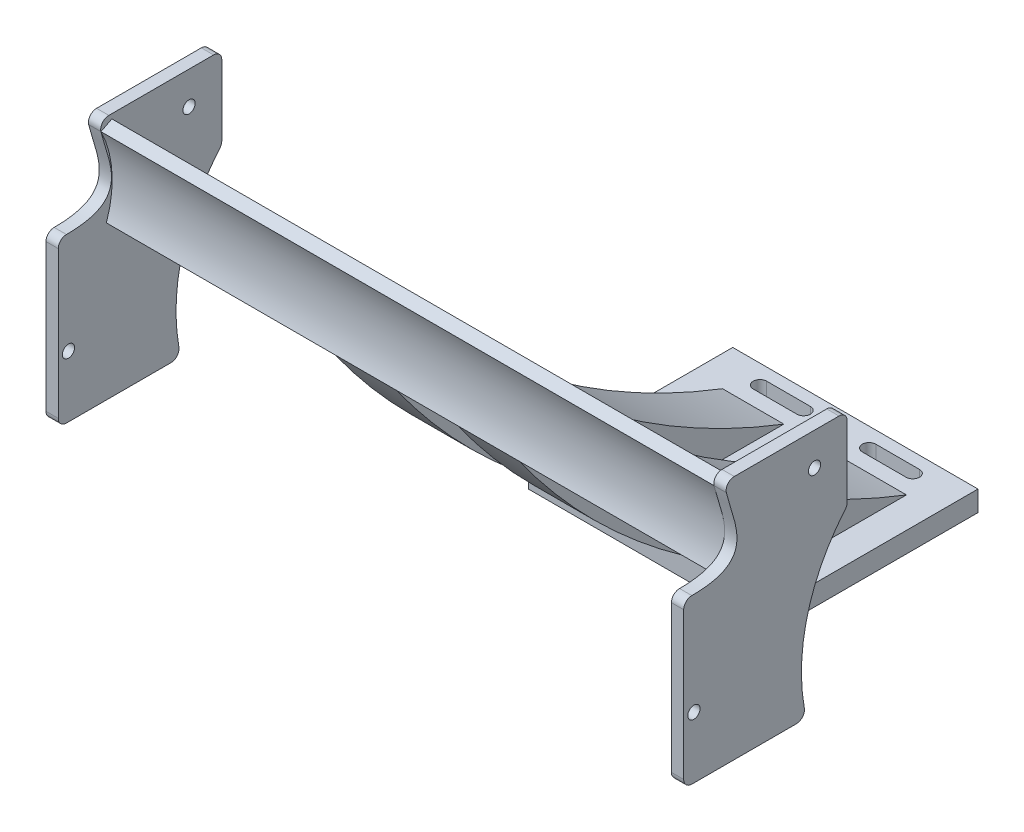
SolidWorks part; units mm, degrees
ref_plane "Front Plane" through (0, 0, 0) normal (0, 0, 1) x (1, 0, 0)
ref_plane "Top Plane" through (0, 0, 0) normal (0, 1, 0) x (1, 0, 0)
ref_plane "Right Plane" through (0, 0, 0) normal (1, 0, 0) x (0, 0, -1)
sketch "Sketch2" plane through (0, 0, 0) normal (1, 0, 0) x (0, 0, -1)
  line L10 (-2.4559, 0) -> (-28, 0)
  line L11 (-30, 2) -> (-30, 37.9594)
  line L14 (-17.6225, 60) -> (8, 60)
  line L16 (10, 58) -> (10, 40.7445)
  arc A8 (9.5236, 39.4489) -> (-0.4873, 2.3531) centre (43.8057, 10.2986) ccw
  arc A9 (10, 40.7445) -> (9.5236, 39.4489) centre (8, 40.7445) cw
  arc A10 (-2.4559, 0) -> (-0.4873, 2.3531) centre (-2.4559, 2) ccw
  arc A11 (-28, 0) -> (-30, 2) centre (-28, 2) cw
  arc A12 (-19.5664, 57.5296) -> (-17.6225, 60) centre (-17.6225, 58) cw
  arc A13 (8, 60) -> (10, 58) centre (8, 58) cw
  arc A14 (-30, 37.9594) -> (-28.0049, 39.9594) centre (-28, 37.9594) cw
  spline S0 degree 3 poles (-19.5664, 57.5296) (-18.6009, 53.5401) (-14.6297, 44.7325) (-20.2091, 39.9783) (-28.0049, 39.9594) knots 0.096883 0.096883 0.096883 0.096883 0.548442 0.966186 0.966186 0.966186 0.966186
  point P9 (10, 40)
  point P12 (0, 0)
  point P15 (-30, 0)
  point P22 (10, 60)
  dimension "D7" = 45
  dimension "D8" = 2
  dimension "D1" = 60
  dimension "D3" = 40
  dimension "D4" = 20
  dimension "D5" = 30
extrude "Boss-Extrude3" add sketch "Sketch2" along normal blind 3
sketch "Sketch3" plane through (0, 0, 0) normal (-1, 0, 0) x (0, 0, 1)
  line L0 (18.228, 37.5296) -> (15.228, 37.5296)
  line L1 (19.5664, 57.5296) -> (16.8897, 58.8843)
  arc A0 (19.5664, 57.5296) -> (18.228, 37.5296) centre (42.4376, 45.9543) ccw
  arc A1 (16.8897, 58.8843) -> (15.228, 37.5296) centre (37.4721, 46.5407) ccw
  point P10 (18.228, 58.2069)
  dimension "D1" = 20
  dimension "D2" = 3
  dimension "D4" = 5
  dimension "D5" = 24
  dimension "D3" = 3
extrude "Boss-Extrude4" add sketch "Sketch3" along normal blind 150
sketch "Sketch6" plane through (0, 0, 0) normal (-1, 0, 0) x (0, 0, 1)
  line L0 (-984.772, 37.5296) -> (49015.228, 37.5296) construction
  line L1 (15.228, -962.4704) -> (15.228, 49037.5296) construction
  arc A0 (14.728, 37.0296) -> (-5.2657, 36.5296) centre (3.2521, 95.9219) cw
  arc A1 (14.728, 34.0296) -> (-5.272, 33.5296) centre (3.6315, 77.64) cw
  arc A2 (14.728, 37.0296) -> (14.728, 34.0296) centre (17.3261, 35.5296) ccw
  arc A3 (-5.2657, 36.5296) -> (-5.272, 33.5296) centre (-8.9769, 35.0373) cw
  dimension "D9" = 45
  dimension "D10" = 60
  dimension "D11" = 3
  dimension "D12" = 4
  dimension "D1" = 20
  dimension "D2" = 20
  dimension "D3" = 0.5
  dimension "D4" = 0.5
  dimension "D5" = 0.5
  dimension "D6" = 1
  dimension "D7" = 3
  dimension "D8" = 3
extrude "Boss-Extrude7" add sketch "Sketch6" along normal blind 150
ref_plane "Plane2" through (-75, 0, 0) normal (-1, 0, 0) x (0, 0, 1)
mirror "Mirror2" about plane through (-75, 0, 0) normal (-1, 0, 0) of "Boss-Extrude3"
ref_plane "Plane5" through (-60, 0, 0) normal (1, 0, 0) x (0, 0, -1)
sketch "Sketch9" plane through (-60, 0, 0) normal (1, 0, 0) x (0, 0, -1)
  line L1 (-1014.9855, -20.4704) -> (48985.0145, -20.4704) construction
  line L2 (0, -1000) -> (0, 49000) construction
  line L3 (50, -20.4704) -> (80, -20.4704)
  arc A1 (-14.728, 34.0296) -> (-14.728, 37.0296) centre (-17.3261, 35.5296) ccw construction
  arc A3 (-14.728, 34.0296) -> (50, -20.4704) centre (123.6848, 132.7306) ccw
  arc A7 (-14.728, 34.0296) -> (5.265, 33.5282) centre (-3.6315, 77.64) ccw construction
  arc A8 (5.272, 33.5296) -> (80, -20.4704) centre (144.5465, 147.5586) ccw
  arc A9 (-14.728, 34.0296) -> (5.272, 33.5296) centre (-3.6315, 77.64) ccw
  dimension "D1" = 56
  dimension "D4" = 180
  dimension "D5" = 170
  dimension "D6" = 45
  dimension "D2" = 50
  dimension "D3" = 30
extrude "Boss-Extrude11" add sketch "Sketch9" against normal mid plane 15
ref_plane "Plane6" through (-75, 0, 0) normal (-1, 0, 0) x (0, 0, 1)
mirror "Mirror3" about plane through (-75, 0, 0) normal (-1, 0, 0) of "Boss-Extrude11"
sketch "Sketch10" plane through (0, -20.4704, 0) normal (0, -1, 0) x (1, 0, 0)
  line L0 (-1097.5, -65) -> (48902.5, -65) construction
  line L1 (-105, -40) -> (-45, -40)
  line L2 (-105, -40) -> (-105, -90)
  line L3 (-105, -90) -> (-45, -90)
  line L4 (-45, -40) -> (-45, -90)
  line L5 (-105, -40) -> (-45, -90) construction
  line L6 (-105, -90) -> (-45, -40) construction
  line L8 (-97.5, -50) -> (-97.5, -80) construction
  line L10 (-75, -1065) -> (-75, 48935) construction
  line L11 (-82.5, -50) -> (-82.5, 14.728) construction
  point P0 (-75, -65)
  point P17 (-97.5, -65)
  dimension "D1" = 50
  dimension "D2" = 60
  dimension "D3" = 7.5
extrude "Boss-Extrude12" add sketch "Sketch10" along normal blind 5
sketch "Sketch11" plane through (0, -20.4704, 0) normal (0, 1, 0) x (1, 0, 0)
  line L0 (-93.7, 85.35) -> (-83, 85.35) construction
  line L1 (-93.7, 87) -> (-83, 87)
  line L2 (-93.7, 83.7) -> (-83, 83.7)
  line L3 (-67, 85.35) -> (-56.3, 85.35) construction
  line L4 (-67, 87) -> (-56.3, 87)
  line L5 (-67, 83.7) -> (-56.3, 83.7)
  line L6 (-75, -910) -> (-75, 49090) construction
  line L7 (-105, 90) -> (-45, 90) construction
  arc A0 (-93.7, 87) -> (-93.7, 83.7) centre (-93.7, 85.35) ccw
  arc A1 (-83, 83.7) -> (-83, 87) centre (-83, 85.35) ccw
  arc A2 (-67, 87) -> (-67, 83.7) centre (-67, 85.35) ccw
  arc A3 (-56.3, 83.7) -> (-56.3, 87) centre (-56.3, 85.35) ccw
  point P2 (-88.35, 85.35)
  point P7 (-61.65, 85.35)
  point P15 (-81.35, 85.35)
  point P19 (-75, 90)
  point P20 (-68.65, 85.35)
  dimension "D1" = 6.35
  dimension "D2" = 6.35
  dimension "D3" = 10.7
  dimension "D4" = 10.7
  dimension "D5" = 3.3
  dimension "D6" = 3.3
  dimension "D7" = 3
extrude "Cut-Extrude1" cut sketch "Sketch11" against normal through all
sketch "Sketch12" plane through (3, 0, 0) normal (1, 0, 0) x (0, 0, -1)
  circle A0 centre (2, 52) radius 1.5
  circle A1 centre (-27.5, 15) radius 1.5
  dimension "D1" = 3
  dimension "D2" = 3
extrude "Cut-Extrude2" cut sketch "Sketch12" against normal through all
